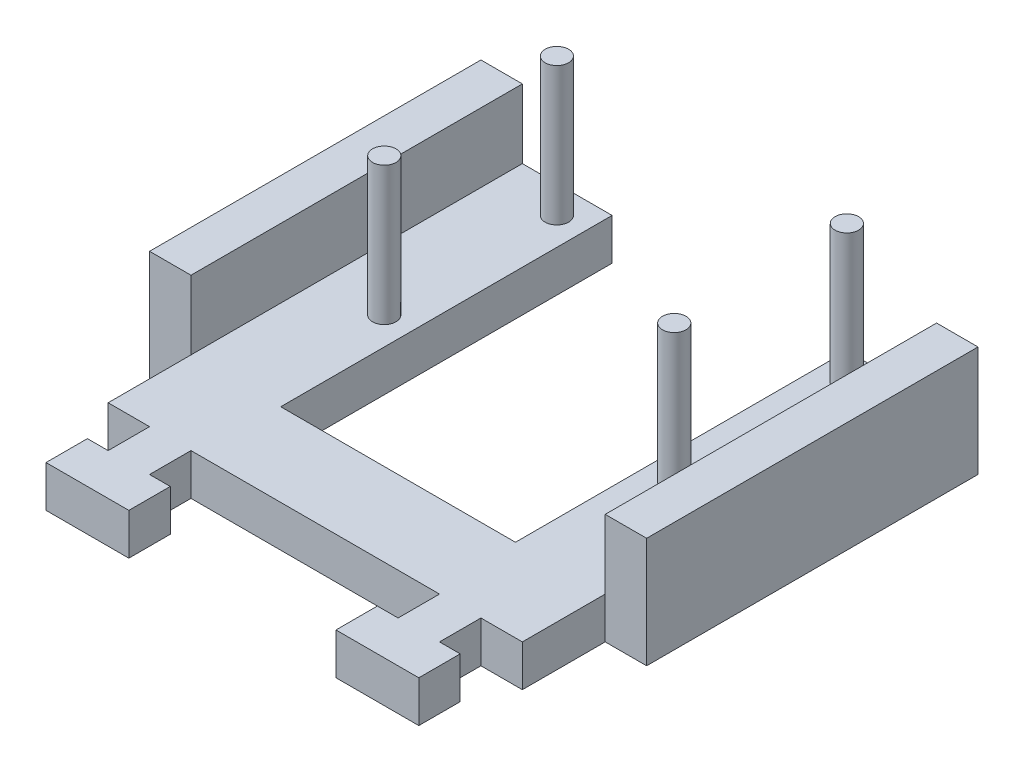
SolidWorks part; units mm, degrees
ref_plane "Front Plane" through (0, 0, 0) normal (0, 0, 1) x (1, 0, 0)
ref_plane "Top Plane" through (0, 0, 0) normal (0, 1, 0) x (1, 0, 0)
ref_plane "Right Plane" through (0, 0, 0) normal (1, 0, 0) x (0, 0, -1)
sketch "Sketch1" plane through (0, 0, 0) normal (0, 1, 0) x (1, 0, 0)
  line L0 (0, 0) -> (3, 0)
  line L1 (3, 0) -> (3, -3)
  line L2 (3, -3) -> (1.5, -3)
  line L3 (1.5, -3) -> (1.5, -6)
  line L4 (1.5, -6) -> (7.5, -6)
  line L5 (7.5, -6) -> (7.5, -3)
  line L6 (7.5, -3) -> (6, -3)
  line L7 (6, -3) -> (6, 0)
  line L8 (6, 0) -> (24, 0)
  line L9 (24, 0) -> (24, -3)
  line L10 (24, -3) -> (22.5, -3)
  line L11 (22.5, -3) -> (22.5, -6)
  line L12 (22.5, -6) -> (28.5, -6)
  line L13 (28.5, -6) -> (28.5, -3)
  line L14 (28.5, -3) -> (27, -3)
  line L15 (27, -3) -> (27, 0)
  line L16 (27, 0) -> (30, 0)
  line L17 (30, 0) -> (30, 6)
  line L18 (30, 6) -> (33, 6)
  line L19 (33, 6) -> (33, 30)
  line L20 (-3, 30) -> (6.5, 30)
  line L21 (-3, 30) -> (-3, 6)
  line L22 (-3, 6) -> (0, 6)
  line L23 (0, 6) -> (0, 0)
  line L24 (6.5, 30) -> (6.5, 6)
  line L25 (6.5, 6) -> (23.5, 6)
  line L26 (23.5, 6) -> (23.5, 30)
  line L27 (23.5, 30) -> (33, 30)
  point P13 (15, 6)
  point P31 (15, 0)
  point P32 (0, 0)
  dimension "D1" = 3
  dimension "D2" = 3
  dimension "D3" = 24
  dimension "D4" = 36
  dimension "D5" = 24
  dimension "D6" = 3
  dimension "D7" = 3
  dimension "D8" = 3
  dimension "D9" = 3
  dimension "D10" = 1.5
  dimension "D11" = 1.5
  dimension "D12" = 3
  dimension "D13" = 3
  dimension "D14" = 1.5
  dimension "D15" = 1.5
  dimension "D16" = 3
  dimension "D17" = 3
  dimension "D18" = 3
  dimension "D19" = 6
  dimension "D20" = 6
  dimension "D21" = 17
  dimension "D22" = 24
extrude "Boss-Extrude1" add sketch "Sketch1" along normal blind 3
sketch "Sketch2" plane through (0, 3, 0) normal (0, 1, 0) x (1, 0, 0)
  line L0 (0, 6) -> (0, 30)
  line L2 (0, 30) -> (-3, 30)
  line L3 (-3, 30) -> (-3, 6)
  line L4 (-3, 6) -> (0, 6)
  line L5 (33, 30) -> (30, 30)
  line L6 (33, 6) -> (33, 30)
  line L7 (30, 30) -> (30, 6)
  line L8 (30, 6) -> (33, 6)
  line L9 (4.5, 28) -> (25.5, 28) construction
  line L10 (6.5, 30) -> (-3, 30) construction
  line L11 (23.5, 6) -> (6.5, 6) construction
  line L12 (33, 30) -> (23.5, 30) construction
  circle A0 centre (4.5, 28) radius 0.85
  circle A1 centre (25.5, 28) radius 0.85
  circle A2 centre (25.5, 15.5) radius 0.85
  circle A3 centre (4.5, 15.5) radius 0.85
  point P3 (0, 0)
  point P4 (0, 0)
  point P25 (0, 0)
  point P26 (15, 28)
  point P28 (0, 0)
  point P32 (15, 6)
  point P33 (0, 0)
  point P36 (0, 0)
  dimension "D2" = 1.7
  dimension "D3" = 1.7
  dimension "D4" = 1.7
  dimension "D5" = 1.7
  dimension "D1" = 3
  dimension "D6" = 21
  dimension "D7" = 2
  dimension "D8" = 12.5
extrude "Boss-Extrude2" add sketch "Sketch2" along normal blind 5
sketch "Sketch3" plane through (0, 8, 0) normal (0, 1, 0) x (1, 0, 0)
  circle A0 centre (4.5, 28) radius 0.85
  circle A1 centre (25.5, 28) radius 0.85
  circle A2 centre (25.5, 15.5) radius 0.85
  circle A3 centre (4.5, 15.5) radius 0.85
  circle A6 centre (25.5, 15.5) radius 0.85 construction
  circle A7 centre (25.5, 28) radius 0.85 construction
  dimension "D1" = 1.7
  dimension "D2" = 1.7
  dimension "D3" = 1.7
  dimension "D4" = 1.7
extrude "Boss-Extrude3" add sketch "Sketch3" along normal blind 5
